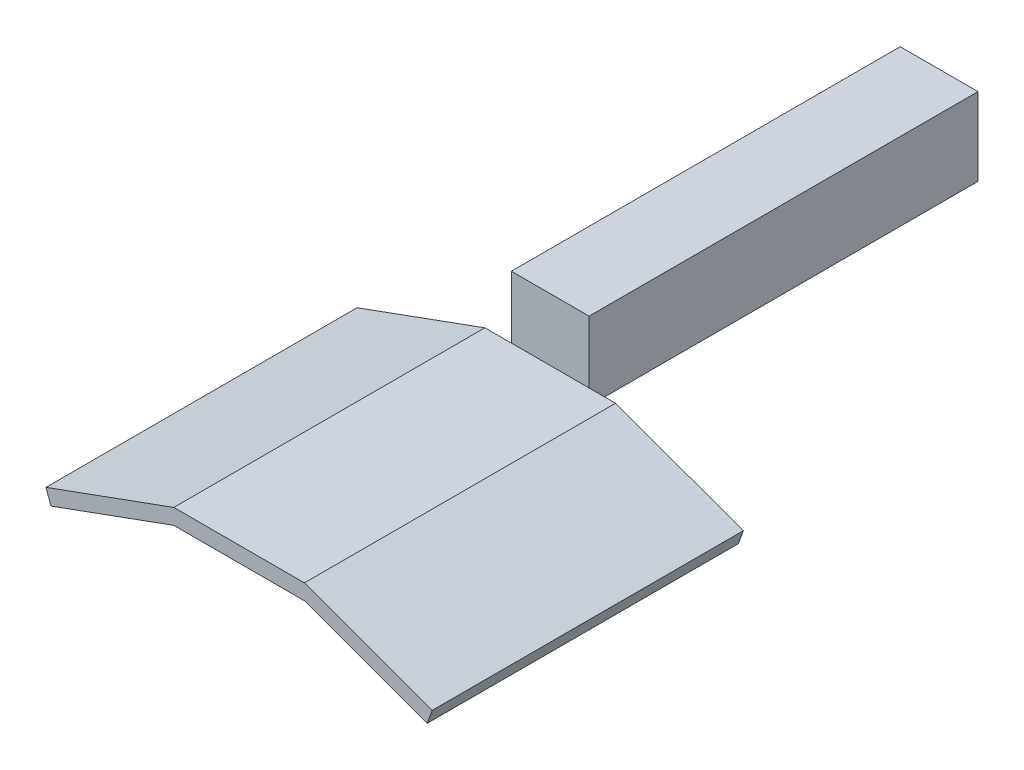
SolidWorks part; units mm, degrees
ref_plane "Front Plane" through (0, 0, 0) normal (0, 0, 1) x (1, 0, 0)
ref_plane "Top Plane" through (0, 0, 0) normal (0, 1, 0) x (1, 0, 0)
ref_plane "Right Plane" through (0, 0, 0) normal (1, 0, 0) x (0, 0, -1)
sketch "Sketch1" plane through (0, 0, 0) normal (0, 0, 1) x (1, 0, 0)
  line L1 (0, 0) -> (100, 0)
  line L2 (0, 0) -> (0, 100)
  line L3 (0, 100) -> (100, 100)
  line L4 (100, 0) -> (100, 100)
  dimension "D1" = 100
extrude "Boss-Extrude1" add sketch "Sketch1" along normal blind 500
sketch "Sketch2" plane through (0, 0, 500) normal (0, 0, 1) x (1, 0, 0)
  line L0 (50, 20) -> (50, 100) construction
  line L1 (-34, 0) -> (134, 0)
  line L2 (-34, 0) -> (-34, 20)
  line L3 (-34, 20) -> (134, 20)
  line L4 (134, 0) -> (134, 20)
  line L5 (100, 100) -> (0, 100) construction
  line L6 (0, 0) -> (100, 0) construction
  dimension "D1" = 168
  dimension "D2" = 20
extrude "Boss-Extrude2" add sketch "Sketch2" along normal blind 400
sketch "Sketch3" plane through (0, 0, 900) normal (0, 0, 1) x (1, 0, 0)
  line L0 (134, 0) -> (291.8684, -57.4594)
  line L1 (291.8684, -57.4594) -> (298.2962, -39.7989)
  line L2 (298.2962, -39.7989) -> (134, 20)
  line L3 (134, 20) -> (134, 0)
  line L4 (50, 0) -> (50, 134.487) construction
  line L5 (-34, 0) -> (134, 0) construction
  line L6 (-198.2962, -39.7989) -> (-34, 20)
  line L7 (-191.8684, -57.4594) -> (-198.2962, -39.7989)
  line L8 (-34, 0) -> (-191.8684, -57.4594)
  line L9 (-34, 20) -> (-34, 0)
  dimension "D1" = 20
  dimension "D2" = 168
extrude "Boss-Extrude3" add sketch "Sketch3" against normal blind 400
